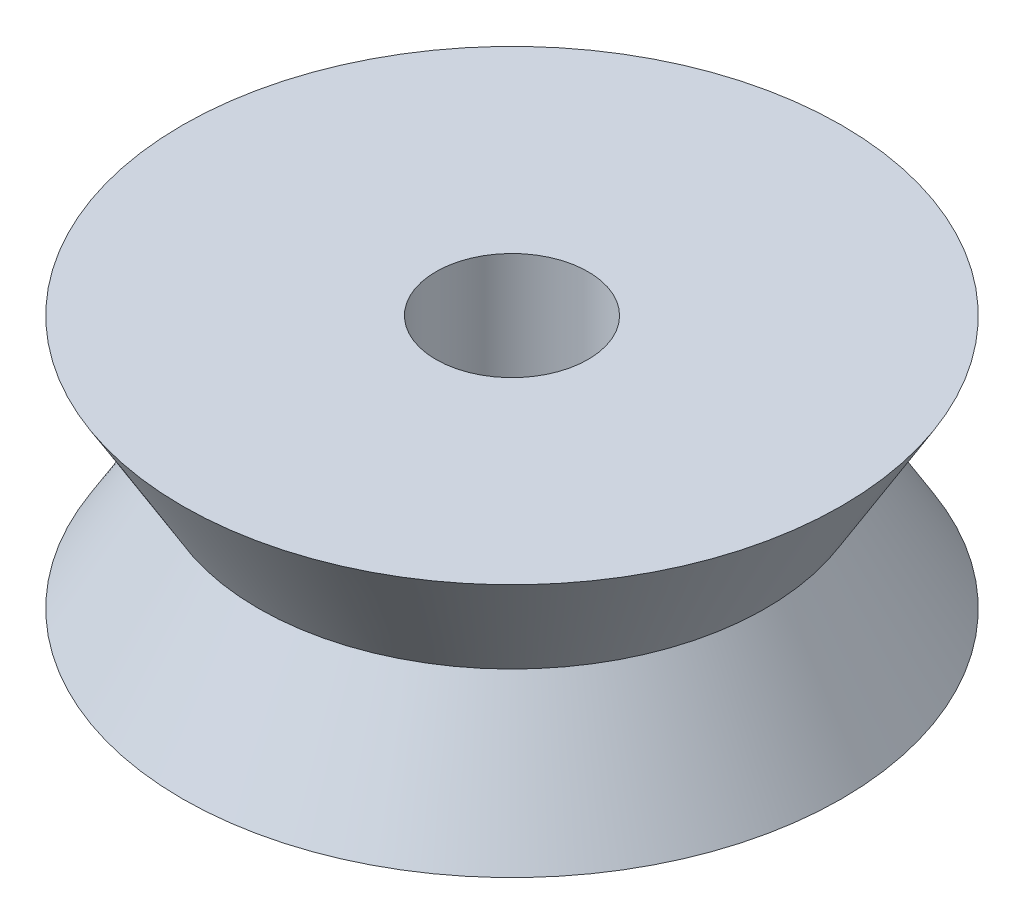
SolidWorks part; units mm, degrees
ref_plane "Alzado" through (0, 0, 0) normal (0, 0, 1) x (1, 0, 0)
ref_plane "Planta" through (0, 0, 0) normal (0, 1, 0) x (1, 0, 0)
ref_plane "Vista lateral" through (0, 0, 0) normal (1, 0, 0) x (0, 0, -1)
sketch "Croquis1" plane through (0, 0, 0) normal (0, 0, 1) x (1, 0, 0)
  line L0 (3, -5) -> (3, 5)
  line L1 (3, 5) -> (13, 5)
  line L2 (13, 5) -> (10, 0)
  line L3 (10, 0) -> (13, -5)
  line L4 (13, -5) -> (3, -5)
  point P0 (0, 0)
  point P2 (10.9639, -4.325)
  point P7 (3, 0)
  dimension "D1" = 10
  dimension "D2" = 10
  dimension "D3" = 3
  dimension "D4" = 3
ref_axis "Eje1" through (0, 5.5, 0) along (0, -1, 0)
revolve "Revolución1" add sketch "Croquis1" angle 360 about axis through (0, 5.5, 0) along (0, -1, 0)
